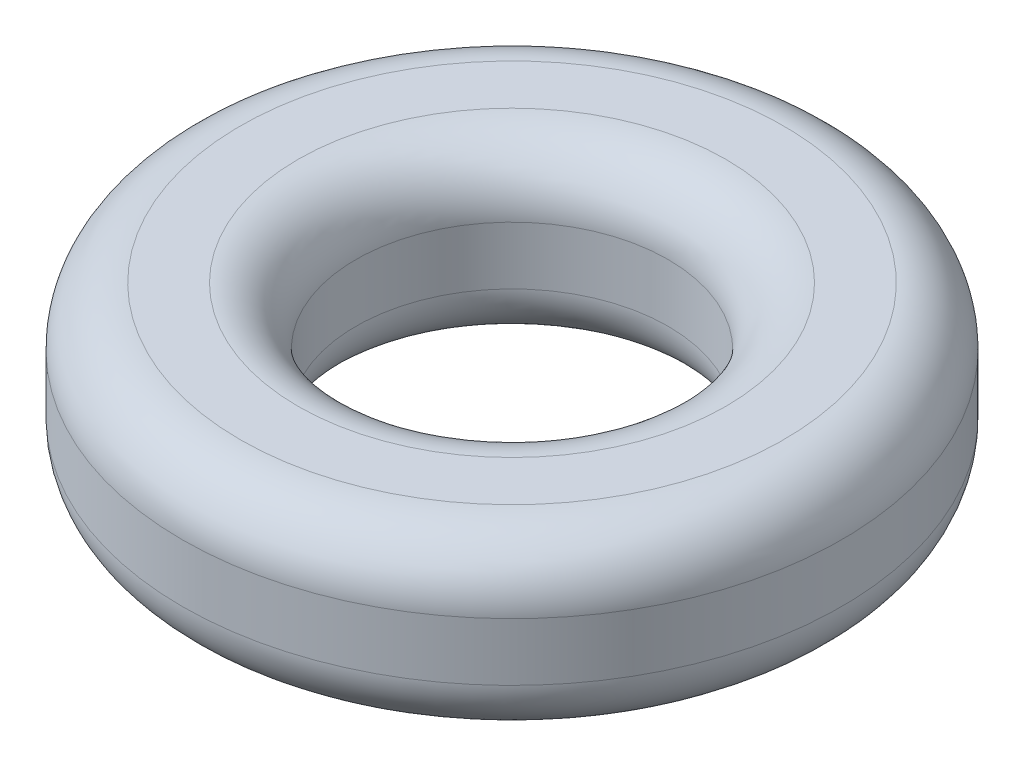
SolidWorks part; units mm, degrees
ref_plane "Front Plane" through (0, 0, 0) normal (0, 0, 1) x (1, 0, 0)
ref_plane "Top Plane" through (0, 0, 0) normal (0, 1, 0) x (1, 0, 0)
ref_plane "Right Plane" through (0, 0, 0) normal (1, 0, 0) x (0, 0, -1)
sketch "Sketch1" plane through (0, 0, 0) normal (0, 1, 0) x (1, 0, 0)
  circle A0 centre (0, 0) radius 1.35
  circle A1 centre (0, 0) radius 2.85
  dimension "D1" = 2.7
  dimension "D2" = 1.5
extrude "Boss-Extrude1" add sketch "Sketch1" along normal blind 1.5
fillet "Fillet1" radius 0.5 4 edges at (0, 0, 2.85) (0, 1.5, 2.85) (0, 0, 1.35) (0, 1.5, 1.35)
